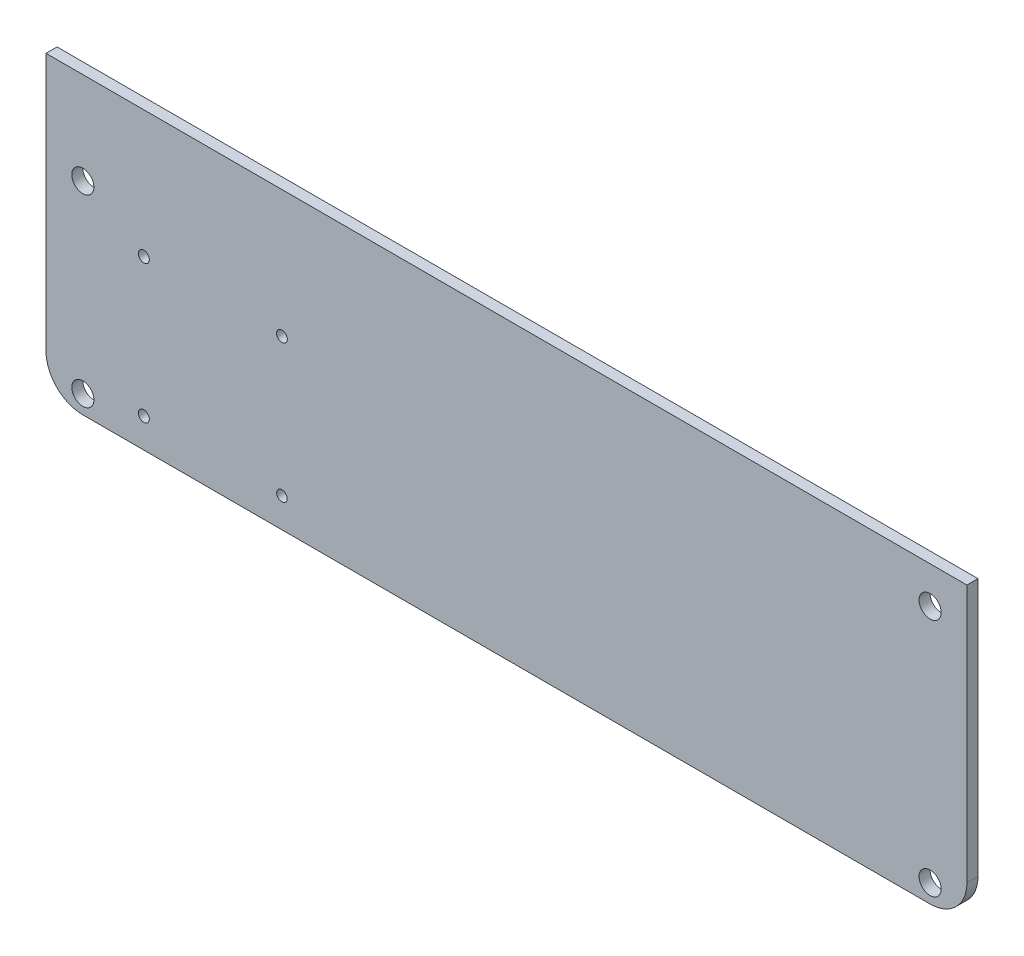
SolidWorks part; units mm, degrees
material "Teck"
ref_plane "Front Plane" through (0, 0, 0) normal (0, 0, 1) x (1, 0, 0)
ref_plane "Top Plane" through (0, 0, 0) normal (0, 1, 0) x (1, 0, 0)
ref_plane "Right Plane" through (0, 0, 0) normal (1, 0, 0) x (0, 0, -1)
sketch "Esquisse1" plane through (0, 0, 0) normal (0, 0, 1) x (1, 0, 0)
  line L1 (0, 0) -> (250, 0)
  line L2 (0, 0) -> (0, -70)
  line L3 (10, -80) -> (240, -80)
  line L4 (250, 0) -> (250, -70)
  arc A0 (250, -70) -> (240, -80) centre (240, -70) cw
  arc A1 (0, -70) -> (10, -80) centre (10, -70) ccw
  point P9 (0, -80)
  dimension "D3" = 10
  dimension "D1" = 250
  dimension "D2" = 80
extrude "Boss.-Extru.1" add sketch "Esquisse1" along normal blind 3
sketch "Esquisse2" plane through (0, 0, 3) normal (0, 0, 1) x (1, 0, 0)
  line L1 (0, 0) -> (0, -70) construction
  line L2 (10, -80) -> (240, -80) construction
  line L3 (250, -70) -> (250, 0) construction
  circle A0 centre (10, -75) radius 3
  circle A1 centre (240, -75) radius 3
  circle A2 centre (240, -10) radius 3
  circle A3 centre (10, -25) radius 3
  point P8 (0, 0)
  dimension "D1" = 6
  dimension "D2" = 50
  dimension "D3" = 10
  dimension "D4" = 10
  dimension "D5" = 5
  dimension "D6" = 10
  dimension "D7" = 5
  dimension "D8" = 65
  dimension "D9" = 10
extrude "Enlèv. mat.-Extru.1" cut sketch "Esquisse2" against normal blind 3
sketch "Esquisse3" plane through (0, 0, 3) normal (0, 0, 1) x (1, 0, 0)
  circle A0 centre (26.5494, -34.5) radius 1.5
  circle A1 centre (64.0494, -34.5) radius 1.4567
  circle A2 centre (64.0494, -72) radius 1.4252
  circle A3 centre (26.5494, -72) radius 1.5
extrude "Enlèv. mat.-Extru.2" cut sketch "Esquisse3" against normal blind 10
